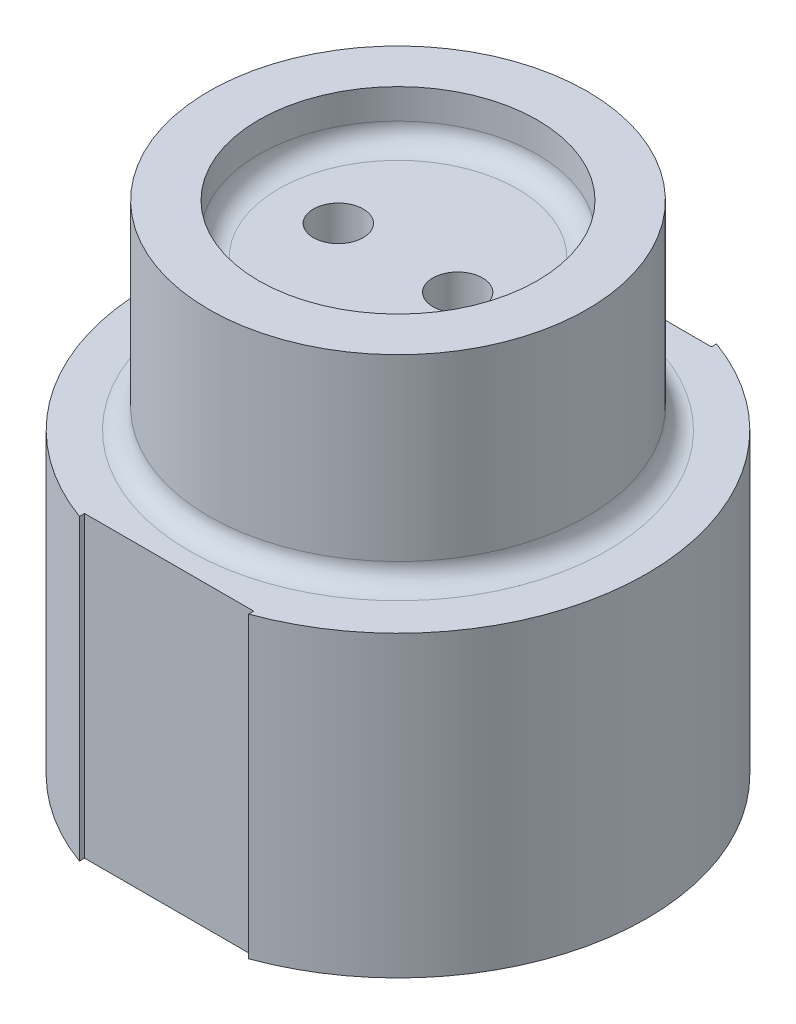
SolidWorks part; units mm, degrees
ref_plane "Front Plane" through (0, 0, 0) normal (0, 0, 1) x (1, 0, 0)
ref_plane "Top Plane" through (0, 0, 0) normal (0, 1, 0) x (1, 0, 0)
ref_plane "Right Plane" through (0, 0, 0) normal (1, 0, 0) x (0, 0, -1)
sketch "Sketch1" plane through (0, 0, 0) normal (0, 0, 1) x (1, 0, 0)
  line L0 (0, 0) -> (2500, 0)
  line L1 (2500, 0) -> (2500, 3000)
  line L2 (2500, 3000) -> (1900, 3000)
  line L3 (1900, 3000) -> (1900, 5000)
  line L4 (0, 500) -> (2000, 500)
  line L5 (2000, 500) -> (2000, 2500)
  line L6 (2000, 2500) -> (1400, 2500)
  line L7 (1400, 2500) -> (1400, 5000)
  line L8 (1900, 5000) -> (1400, 5000)
  line L9 (0, 500) -> (0, 0)
  line L10 (0, 0) -> (0, 5427.2208) construction
  dimension "D1" = 2500
  dimension "D2" = 3000
  dimension "D3" = 2000
  dimension "D4" = 600
  dimension "D5" = 500
revolve "Revolve1" add sketch "Sketch1" angle 360 about L10
ref_plane "Plane1" through (0, 4500, 0) normal (0, 1, 0) x (1, 0, 0)
sketch "Sketch2" plane through (0, 4500, 0) normal (0, 1, 0) x (1, 0, 0)
  circle A0 centre (0, 0) radius 1400
extrude "Boss-Extrude1" add sketch "Sketch2" against normal blind 300
sketch "Sketch3" plane through (0, 4500, 0) normal (0, 1, 0) x (1, 0, 0)
  circle A0 centre (600, 0) radius 250
  circle A1 centre (600, 0) radius 350
  point P2 (0, 0)
  dimension "D2" = 500
  dimension "D1" = 600
  dimension "D3" = 100
sketch "Sketch4" plane through (0, 0, 0) normal (0, 0, 1) x (1, 0, 0)
  line L0 (600, 4500) -> (600, 2000)
  line L1 (600, 2000) -> (1300, 2000)
  line L2 (1300, 2000) -> (1300, 0)
  line L5 (-2500, 0) -> (2500, 0) construction
  point P3 (0, 0)
  point P6 (0, 0)
  point P7 (1300, 515.7006)
  point P8 (0, 0)
  point P11 (1300, 500)
  point P12 (0, 0)
  point P13 (0, 0)
  point P14 (1300, 0)
  dimension "D1" = 2000
  dimension "D2" = 700
sweep "Sweep1" add profiles "Sketch3" path "Sketch4"
sketch "Sketch5" plane through (0, 500, 0) normal (0, 1, 0) x (1, 0, 0)
  circle A0 centre (1300, 0) radius 250
  circle A1 centre (1300, 0) radius 250 construction
extrude "Cut-Extrude1" cut sketch "Sketch5" against normal through all
sketch "Sketch6" plane through (0, 4200, 0) normal (0, -1, 0) x (1, 0, 0)
  circle A0 centre (600, 0) radius 250
  circle A1 centre (600, 0) radius 250 construction
extrude "Cut-Extrude2" cut sketch "Sketch6" against normal through all contours A0
mirror "Mirror2" about plane through (0, 0, 0) normal (1, 0, 0) of "Cut-Extrude1", "Cut-Extrude2", "Sweep1"
ref_plane "Plane2" through (0, 0, 2500) normal (0, 0, 1) x (1, 0, 0)
sketch "Sketch7" plane through (0, 0, 2500) normal (0, 0, 1) x (1, 0, 0)
  line L0 (-2500, 0) -> (2500, 0) construction
  line L1 (-850, 0) -> (850, 0)
  line L2 (-850, 0) -> (-850, 3000)
  line L3 (-850, 3000) -> (850, 3000)
  line L4 (850, 0) -> (850, 3000)
  line L5 (2500, 3000) -> (-2500, 3000) construction
  dimension "D1" = 1700
extrude "Cut-Extrude3" cut sketch "Sketch7" against normal blind 200
mirror "Mirror3" about plane through (0, 0, 0) normal (0, 0, 1) of "Cut-Extrude3"
fillet "Fillet1" radius 200 2 edges at (0, 4500, 1400) (0, 3000, -1900)
